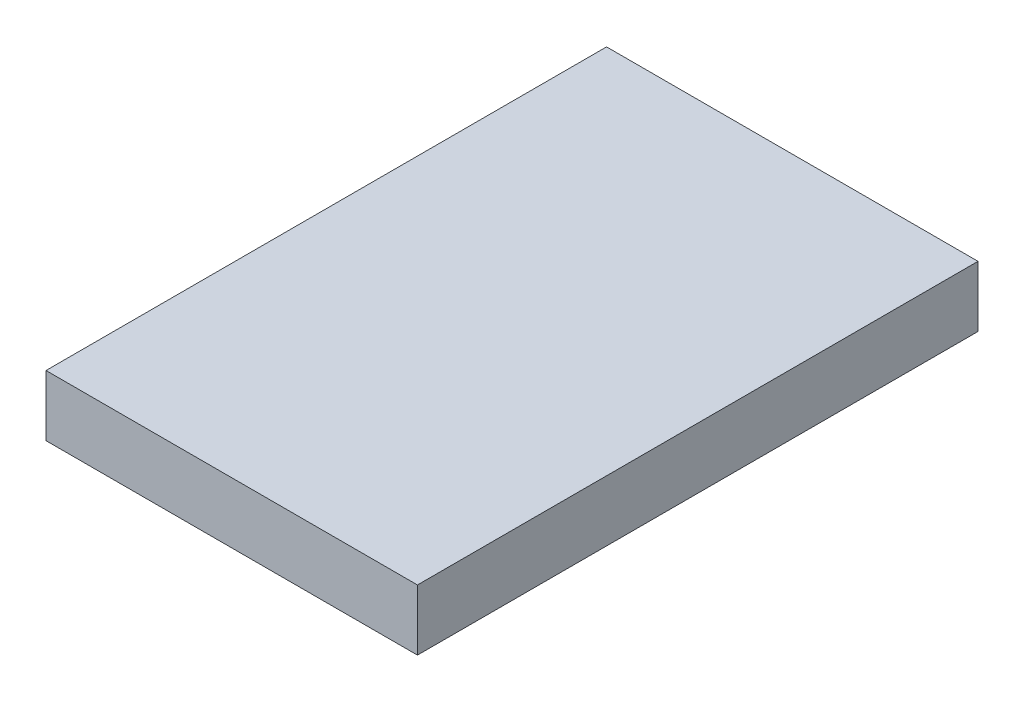
SolidWorks part; units mm, degrees
material "PS Medium/High Flow"
ref_plane "Front Plane" through (0, 0, 0) normal (0, 0, 1) x (1, 0, 0)
ref_plane "Top Plane" through (0, 0, 0) normal (0, 1, 0) x (1, 0, 0)
ref_plane "Right Plane" through (0, 0, 0) normal (1, 0, 0) x (0, 0, -1)
sketch "Sketch1" plane through (0, 0, 0) normal (0, 1, 0) x (1, 0, 0)
  line L1 (-27.5, -41.5) -> (27.5, -41.5)
  line L2 (-27.5, -41.5) -> (-27.5, 41.5)
  line L3 (-27.5, 41.5) -> (27.5, 41.5)
  line L4 (27.5, -41.5) -> (27.5, 41.5)
  line L5 (-27.5, -41.5) -> (27.5, 41.5) construction
  line L6 (-27.5, 41.5) -> (27.5, -41.5) construction
  point P0 (0, 0)
  dimension "D1" = 55
  dimension "D2" = 83
extrude "Boss-Extrude1" add sketch "Sketch1" along normal blind 9
